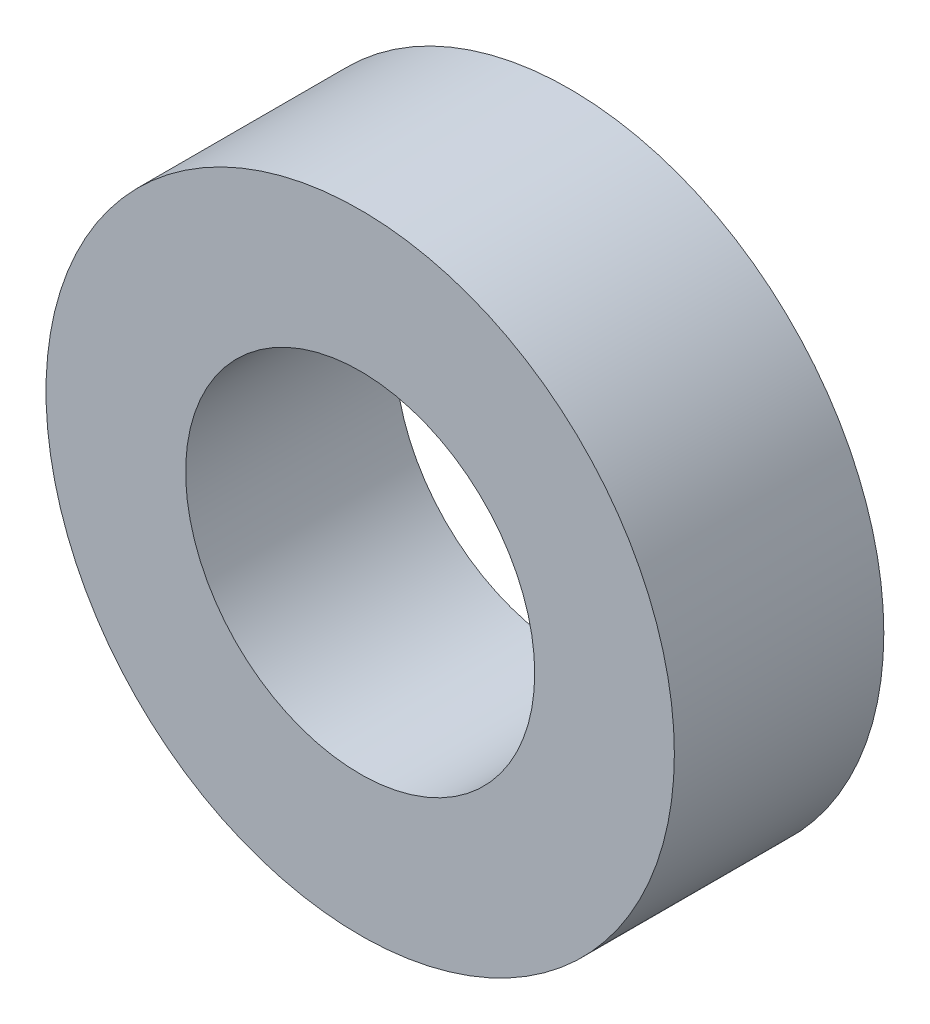
SolidWorks part; units mm, degrees
ref_plane "Front Plane" through (0, 0, 0) normal (0, 0, 1) x (1, 0, 0)
ref_plane "Top Plane" through (0, 0, 0) normal (0, 1, 0) x (1, 0, 0)
ref_plane "Right Plane" through (0, 0, 0) normal (1, 0, 0) x (0, 0, -1)
sketch "Sketch1" plane through (0, 0, 0) normal (0, 0, 1) x (1, 0, 0)
  circle A0 centre (0, 0) radius 5
  circle A1 centre (0, 0) radius 9
  dimension "D1" = 18
  dimension "D2" = 10
extrude "Boss-Extrude1" add sketch "Sketch1" along normal blind 6
